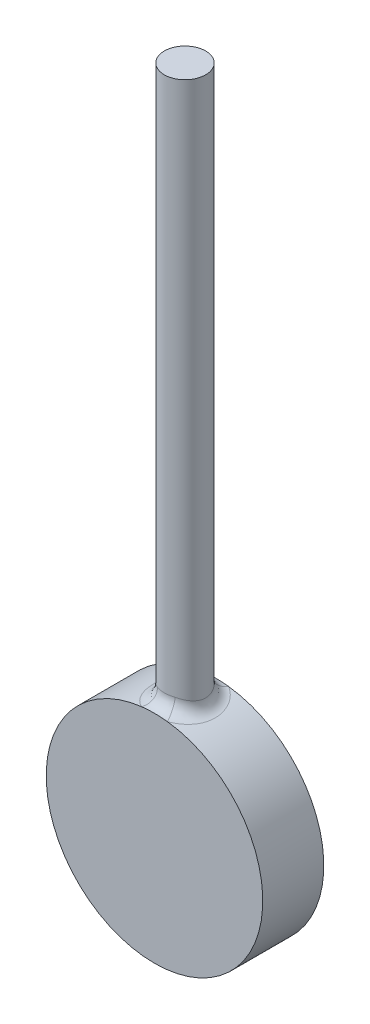
SolidWorks part; units mm, degrees
ref_plane "Front" through (0, 0, 0) normal (0, 0, 1) x (1, 0, 0)
ref_plane "Top" through (0, 0, 0) normal (0, 1, 0) x (1, 0, 0)
ref_plane "Right" through (0, 0, 0) normal (1, 0, 0) x (0, 0, -1)
sketch "Sketch1" plane through (0, 0, 0) normal (0, 0, 1) x (1, 0, 0)
  circle A0 centre (0, 0) radius 4.191
  circle A1 centre (0, 0) radius 1.905 construction
  dimension "D1" = 8.382
  dimension "D2" = 3.81
extrude "Boss-Extrude1" add sketch "Sketch1" along normal mid plane 2.3622
sketch "Sketch2" plane through (0, 0, 0) normal (0, 1, 0) x (1, 0, 0)
  circle A0 centre (0, 0) radius 0.8001
  dimension "D1" = 1.6002
extrude "Boss-Extrude2" add sketch "Sketch2" along normal blind 25.4
fillet "Fillet1" radius 0.508 1 edges at (0.1678, 4.1876, 0.7823)
